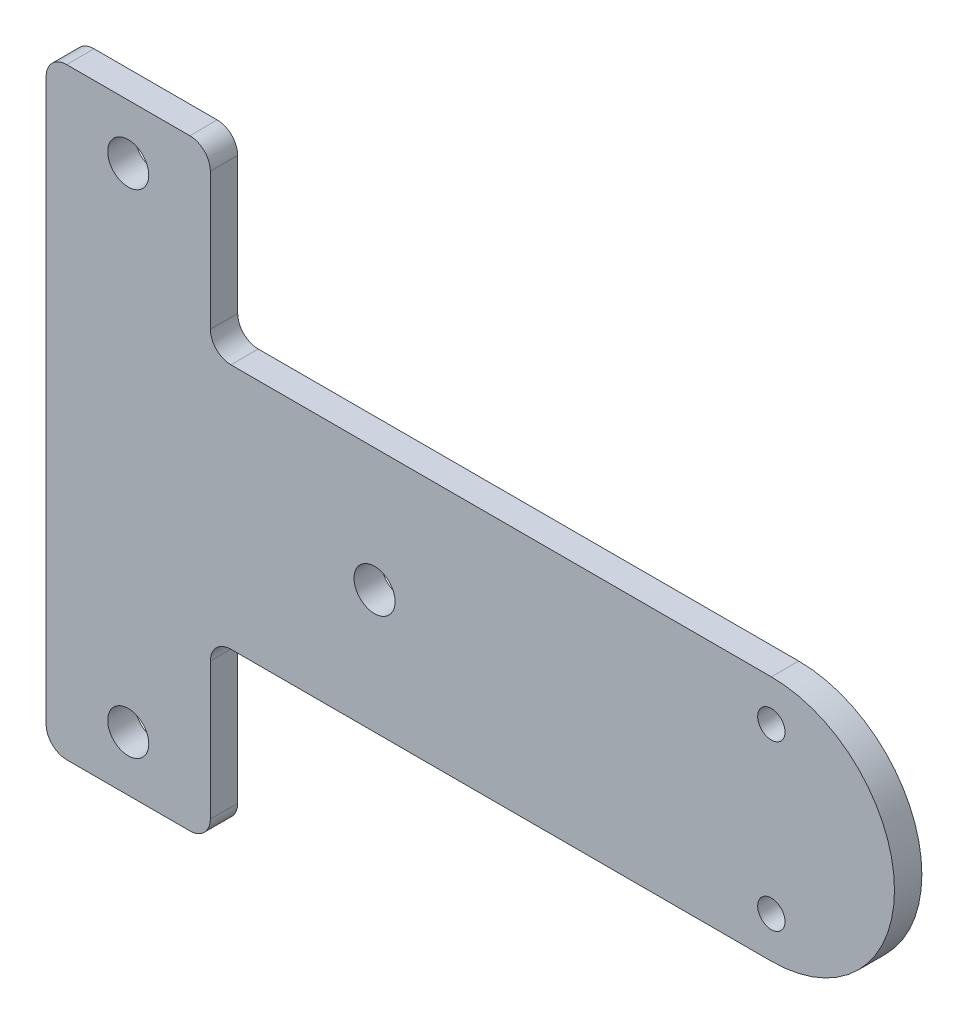
SolidWorks part; units mm, degrees
ref_plane "前视基准面" through (0, 0, 0) normal (0, 0, 1) x (1, 0, 0)
ref_plane "上视基准面" through (0, 0, 0) normal (0, 1, 0) x (1, 0, 0)
ref_plane "右视基准面" through (0, 0, 0) normal (1, 0, 0) x (0, 0, -1)
sketch "草图1" plane through (0, 0, 0) normal (0, 0, 1) x (1, 0, 0)
  line L0 (-1.7236, -4.3699) -> (-1.7236, 1.6301)
  line L1 (-1.7236, -13.3699) -> (-42.7236, -13.3699)
  line L2 (-1.7236, 4.6301) -> (-42.7236, 4.6301)
  line L3 (-42.7236, 4.6301) -> (-42.7236, 17.6301)
  line L4 (-42.7236, 17.6301) -> (-54.7236, 17.6301)
  line L5 (-54.7236, 17.6301) -> (-54.7236, -26.3699)
  line L6 (-54.7236, -26.3699) -> (-42.7236, -26.3699)
  line L7 (-42.7236, -26.3699) -> (-42.7236, -13.3699)
  line L8 (-1.7236, -4.3699) -> (-30.7236, -4.3699) construction
  line L9 (-30.7236, -4.3699) -> (-48.7236, -4.3699) construction
  line L10 (-48.7236, -4.3699) -> (-48.7236, 13.6301) construction
  circle A1 centre (-30.7236, -4.3699) radius 1.5
  circle A2 centre (-48.7236, 13.6301) radius 1.5
  circle A3 centre (-48.7236, -22.3699) radius 1.5
  circle A4 centre (-1.7236, 1.6301) radius 1
  circle A8 centre (-1.7236, -4.3699) radius 9 construction
  arc A9 (-1.7236, 4.6301) -> (-1.7236, -13.3699) centre (-1.7236, -4.3699) cw
  circle A10 centre (-1.7236, -10.3699) radius 1
  dimension "D1" = 3
  dimension "D3" = 2
  dimension "D5" = 36
  dimension "D4" = 6
  dimension "D2" = 6
  dimension "D6" = 18
  dimension "D7" = 12
  dimension "D8" = 29
  dimension "D9" = 6
  dimension "D10" = 18
  dimension "D11" = 4
extrude "凸台-拉伸1" add sketch "草图1" along normal blind 2
fillet "圆角1" radius 1.5 6 edges at (-54.7236, 17.6301, 1) (-42.7236, 17.6301, 1) (-42.7236, 4.6301, 1) (-42.7236, -13.3699, 1) (-42.7236, -26.3699, 1) (-54.7236, -26.3699, 1)
